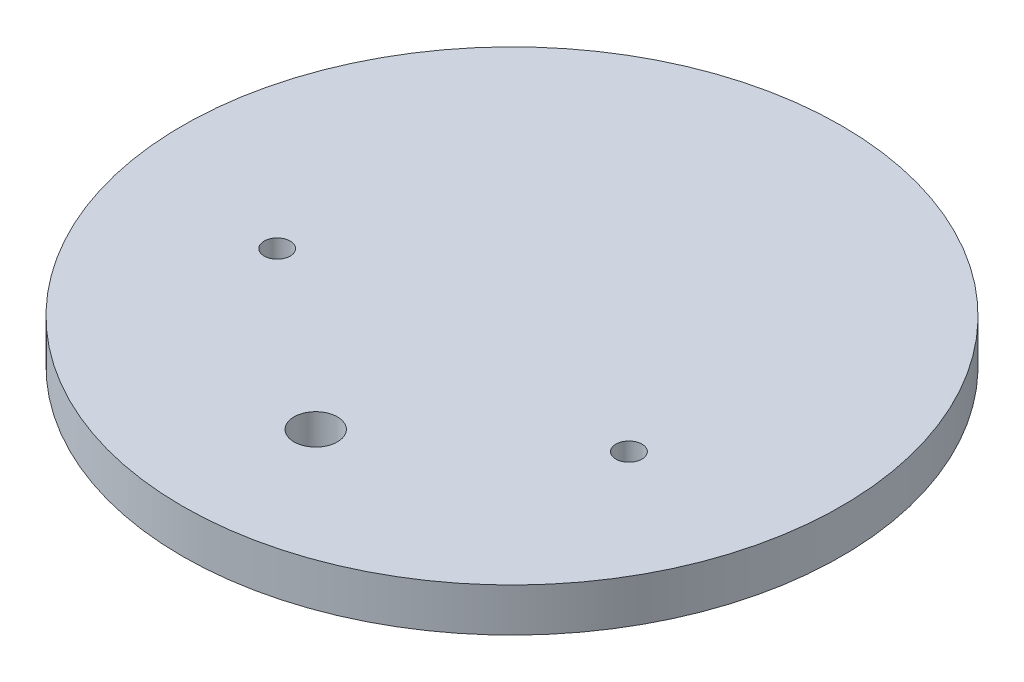
SolidWorks part; units mm, degrees
ref_plane "Front Plane" through (0, 0, 0) normal (0, 0, 1) x (1, 0, 0)
ref_plane "Top Plane" through (0, 0, 0) normal (0, 1, 0) x (1, 0, 0)
ref_plane "Right Plane" through (0, 0, 0) normal (1, 0, 0) x (0, 0, -1)
sketch "Sketch1" plane through (0, 0, 0) normal (0, 1, 0) x (1, 0, 0)
  line L0 (20.2619, -6.7987) -> (-20.2381, -6.7987) construction
  line L1 (0.0119, -6.7987) -> (0.0119, 0.0013) construction
  circle A0 centre (0, 0) radius 37.95
  circle A3 centre (-20.2381, -6.7987) radius 1.5
  circle A4 centre (20.2619, -6.7987) radius 1.5
  circle A5 centre (0.0119, -22.6162) radius 2.5
  point P8 (0.0119, -6.7987)
  dimension "D1" = 75.9
  dimension "D2" = 3
  dimension "D5" = 5
  dimension "D3" = 40.5
  dimension "D4" = 6.8
extrude "Boss-Extrude1" add sketch "Sketch1" along normal blind 5
